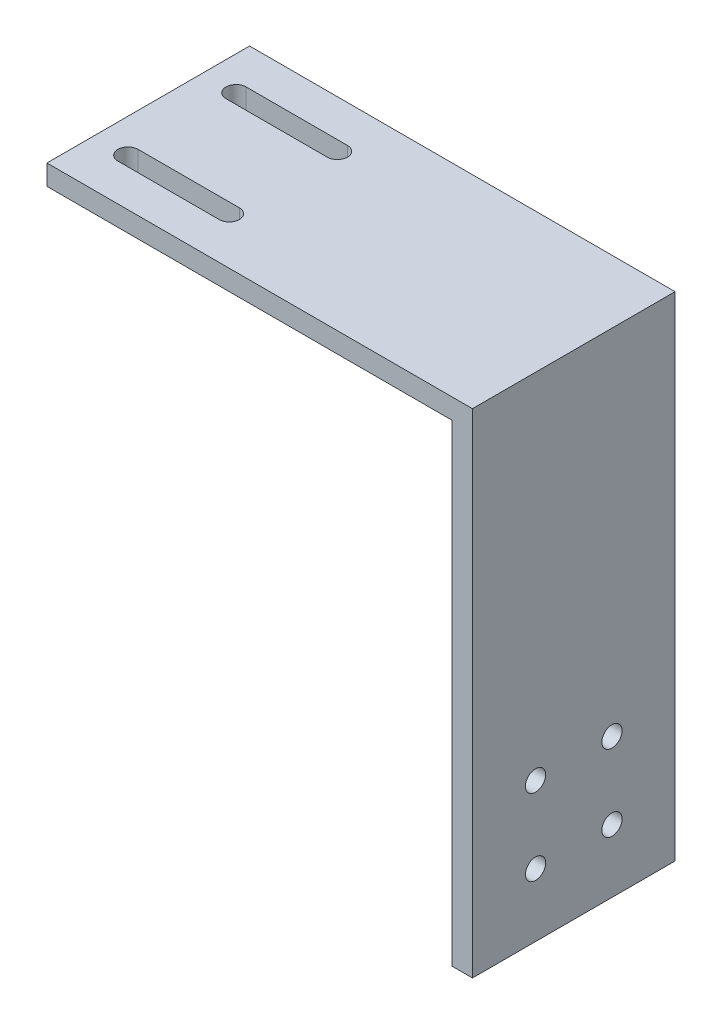
SolidWorks part; units mm, degrees
ref_plane "Alzado" through (0, 0, 0) normal (0, 0, 1) x (1, 0, 0)
ref_plane "Planta" through (0, 0, 0) normal (0, 1, 0) x (1, 0, 0)
ref_plane "Vista lateral" through (0, 0, 0) normal (1, 0, 0) x (0, 0, -1)
sketch "Croquis1" plane through (0, 0, 0) normal (0, 0, 1) x (1, 0, 0)
  line L0 (-64.9286, 65.1357) -> (-64.9286, 62.1357)
  line L1 (-64.9286, 62.1357) -> (-4.9286, 62.1357)
  line L2 (-4.9286, 62.1357) -> (-4.9286, -7.8643)
  line L3 (-4.9286, -7.8643) -> (-1.9286, -7.8643)
  line L4 (-1.9286, -7.8643) -> (-1.9286, 65.1357)
  line L5 (-1.9286, 65.1357) -> (-64.9286, 65.1357)
  dimension "D1" = 3
  dimension "D2" = 3
  dimension "D3" = 60
  dimension "D4" = 70
extrude "Saliente-Extruir1" add sketch "Croquis1" along normal blind 30
sketch "Croquis2" plane through (0, 65.1357, 0) normal (0, 1, 0) x (1, 0, 0)
  line L0 (-64.9286, -15) -> (-1.9286, -15) construction
  line L1 (-64.9286, -30) -> (-64.9286, 0) construction
  line L2 (-1.9286, -30) -> (-1.9286, 0) construction
  line L3 (-64.9286, -15) -> (-64.9286, 0) construction
  line L4 (-64.9286, -7) -> (-44.1808, -7) construction
  line L5 (-59.9286, -24.5) -> (-44.9286, -24.5)
  line L6 (-59.9286, -8.5) -> (-44.9286, -8.5)
  line L7 (-59.9286, -8.5) -> (-59.9286, -5.5) construction
  line L8 (-59.9286, -5.5) -> (-44.9286, -5.5)
  line L9 (-44.9286, -8.5) -> (-44.9286, -5.5) construction
  line L10 (-59.9286, -21.5) -> (-44.9286, -21.5)
  line L11 (-52.9086, -15) -> (-44.9086, -23) construction
  line L12 (-44.9286, -23) -> (-59.9286, -23) construction
  line L13 (-52.9086, -15) -> (-60.9086, -23) construction
  line L14 (-52.9086, -15) -> (-60.9086, -7) construction
  line L15 (-52.9086, -15) -> (-44.9086, -7) construction
  arc A0 (-59.9286, -8.5) -> (-59.9286, -5.5) centre (-59.9286, -7) cw
  arc A1 (-44.9286, -8.5) -> (-44.9286, -5.5) centre (-44.9286, -7) ccw
  arc A2 (-59.9286, -21.5) -> (-59.9286, -24.5) centre (-59.9286, -23) ccw
  arc A3 (-44.9286, -21.5) -> (-44.9286, -24.5) centre (-44.9286, -23) cw
  circle A4 centre (-52.9086, -15) radius 1.5299 construction
  point P27 (-52.9086, -15)
  point P30 (-52.9086, -15)
  dimension "D1" = 3
  dimension "D2" = 1.5
  dimension "D3" = 15
  dimension "D4" = 5
  dimension "D5" = 8
  dimension "D6" = 8
  dimension "D7" = 45
  dimension "D8" = 4
extrude "Cortar-Extruir1" cut sketch "Croquis2" against normal up to vertex (3 mm away)
sketch "Croquis3" plane through (-4.9286, 0, 0) normal (-1, 0, 0) x (0, 0, 1)
  line L0 (30, -7.8643) -> (0, -7.8643) construction
  line L1 (15, 7.1357) -> (20.6569, 1.4789) construction
  circle A0 centre (15, 7.1357) radius 2.7158 construction
  circle A1 centre (20.6569, 1.4789) radius 1.5
  circle A2 centre (9.3431, 1.4789) radius 1.5
  circle A3 centre (9.3431, 12.7926) radius 1.5
  circle A4 centre (20.6569, 12.7926) radius 1.5
  point P14 (15, 7.1357)
  dimension "D1" = 15
  dimension "D3" = 3
  dimension "D2" = 8
  dimension "D4" = 4
extrude "Cortar-Extruir2" cut sketch "Croquis3" against normal up to vertex (3 mm away)
